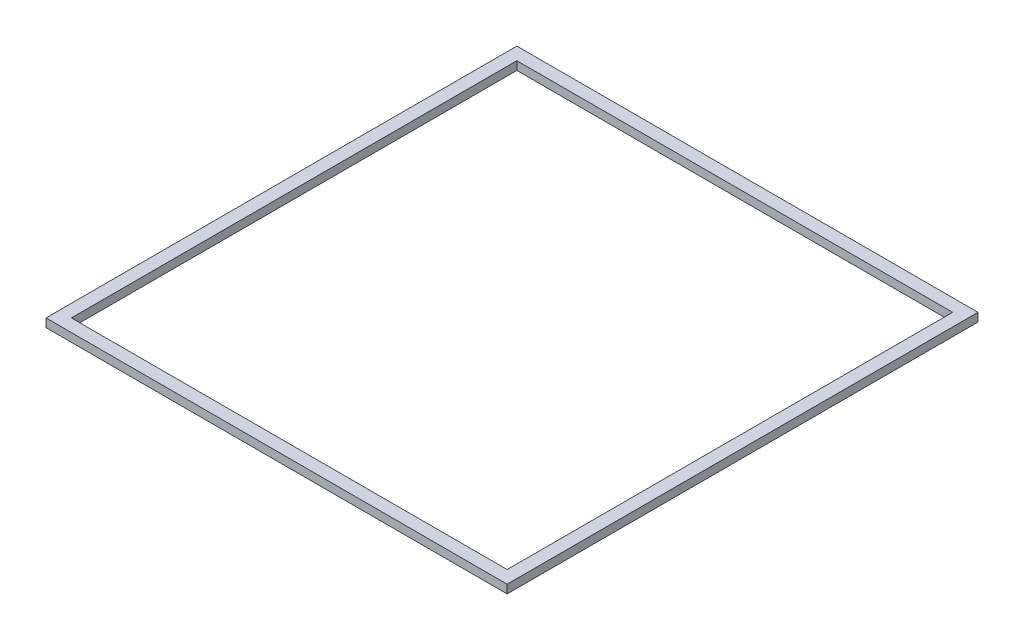
SolidWorks part; units mm, degrees
material "Silicon Rubber"
ref_plane "Front Plane" through (0, 0, 0) normal (0, 0, 1) x (1, 0, 0)
ref_plane "Top Plane" through (0, 0, 0) normal (0, 1, 0) x (1, 0, 0)
ref_plane "Right Plane" through (0, 0, 0) normal (1, 0, 0) x (0, 0, -1)
sketch "Sketch1" plane through (0, 0, 0) normal (0, 1, 0) x (1, 0, 0)
  line L0 (2.3813, 86.0312) -> (84.2062, 86.0312)
  line L1 (0, 0) -> (86.5875, 0)
  line L2 (0, 0) -> (0, 88.4125)
  line L3 (0, 88.4125) -> (86.5875, 88.4125)
  line L4 (86.5875, 0) -> (86.5875, 88.4125)
  line L9 (84.2062, 2.3813) -> (84.2062, 86.0312)
  line L10 (2.3813, 2.3813) -> (84.2062, 2.3813)
  line L11 (2.3813, 2.3813) -> (2.3813, 86.0312)
  dimension "D1" = 86.5875
  dimension "D2" = 88.4125
  dimension "D3" = 2.3813
extrude "Boss-Extrude1" add sketch "Sketch1" along normal blind 1.5875
